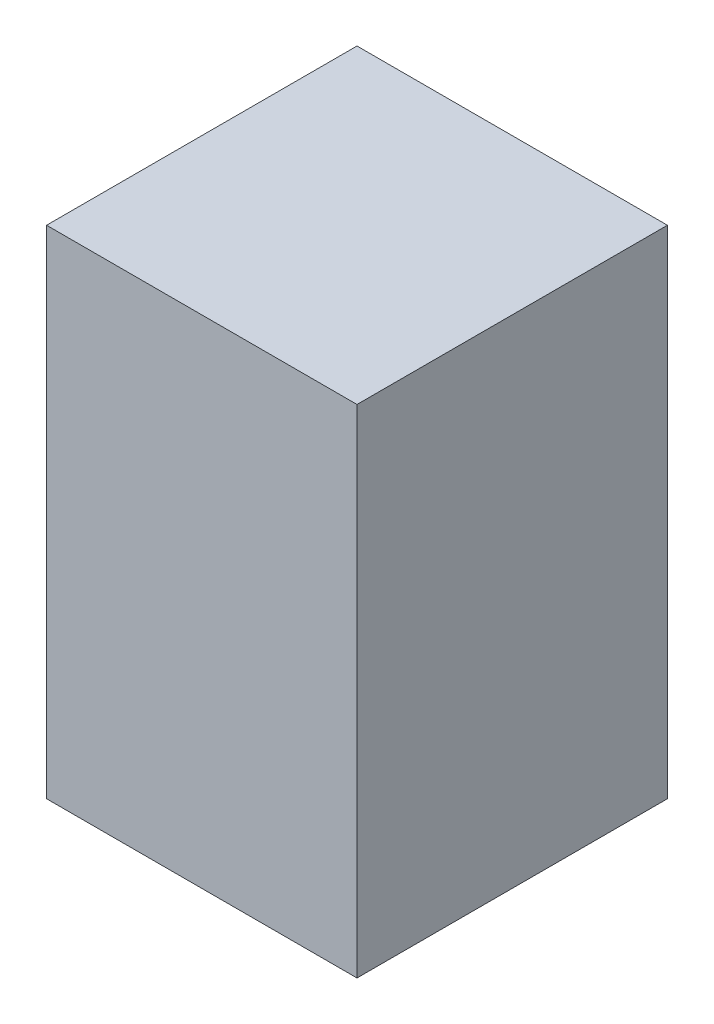
SolidWorks part; units mm, degrees
ref_plane "Front Plane" through (0, 0, 0) normal (0, 0, 1) x (1, 0, 0)
ref_plane "Top Plane" through (0, 0, 0) normal (0, 1, 0) x (1, 0, 0)
ref_plane "Right Plane" through (0, 0, 0) normal (1, 0, 0) x (0, 0, -1)
sketch "Sketch1" plane through (0, 0, 0) normal (0, 1, 0) x (1, 0, 0)
  line L1 (-195.0357, 176.8929) -> (185.9643, 176.8929)
  line L2 (-195.0357, 176.8929) -> (-195.0357, -204.1071)
  line L3 (-195.0357, -204.1071) -> (185.9643, -204.1071)
  line L4 (185.9643, 176.8929) -> (185.9643, -204.1071)
  dimension "D1" = 381
  dimension "D2" = 381
extrude "Boss-Extrude1" add sketch "Sketch1" along normal blind 609.6
